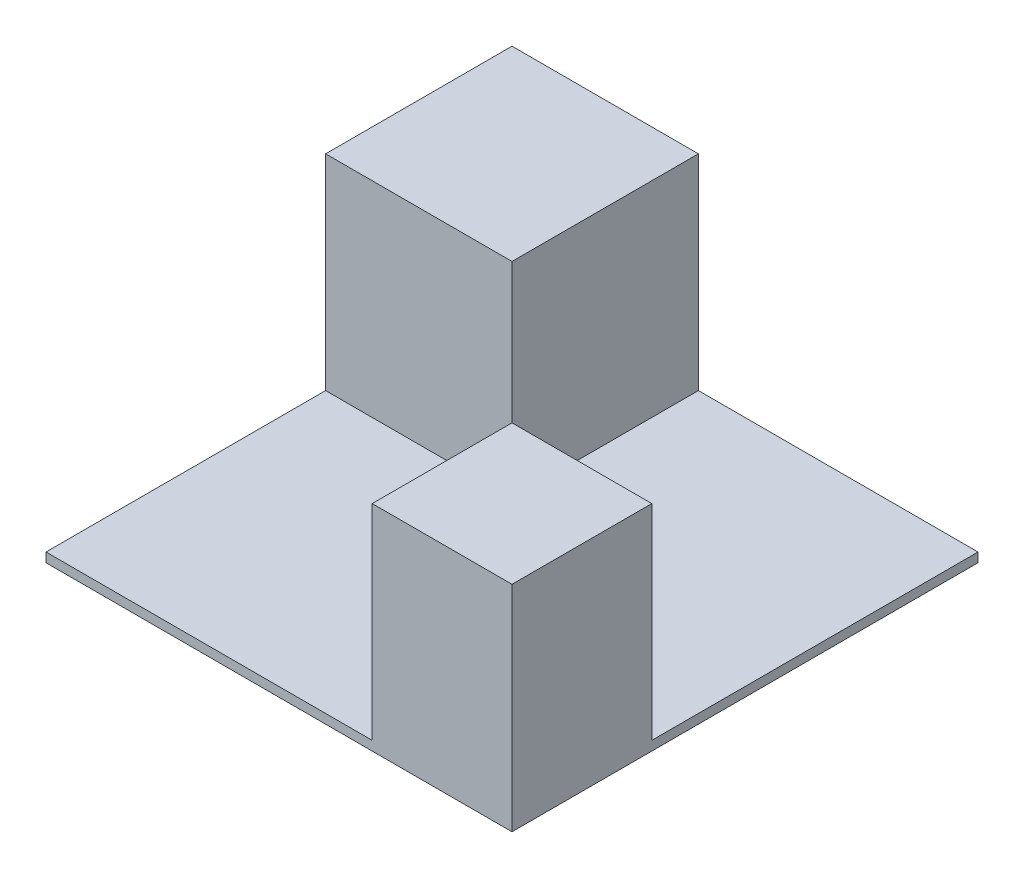
SolidWorks part; units mm, degrees
ref_plane "Front Plane" through (0, 0, 0) normal (0, 0, 1) x (1, 0, 0)
ref_plane "Top Plane" through (0, 0, 0) normal (0, 1, 0) x (1, 0, 0)
ref_plane "Right Plane" through (0, 0, 0) normal (1, 0, 0) x (0, 0, -1)
sketch "Sketch1" plane through (0, 0, 0) normal (0, 1, 0) x (1, 0, 0)
  line L1 (0, 0) -> (50, 0)
  line L2 (0, 0) -> (0, 50)
  line L3 (0, 50) -> (50, 50)
  line L4 (50, 0) -> (50, 50)
  dimension "D1" = 50
extrude "Boss-Extrude1" add sketch "Sketch1" along normal blind 1
sketch "Sketch2" plane through (0, 1, 0) normal (0, 1, 0) x (1, 0, 0)
  line L1 (0, 50) -> (20, 50)
  line L2 (0, 50) -> (0, 30)
  line L3 (0, 30) -> (20, 30)
  line L4 (20, 50) -> (20, 30)
  line L5 (50, 0) -> (35, 0)
  line L6 (50, 0) -> (50, 15)
  line L7 (50, 15) -> (35, 15)
  line L8 (35, 0) -> (35, 15)
  dimension "D1" = 20
  dimension "D2" = 15
extrude "Boss-Extrude2" add sketch "Sketch2" along normal blind 22
